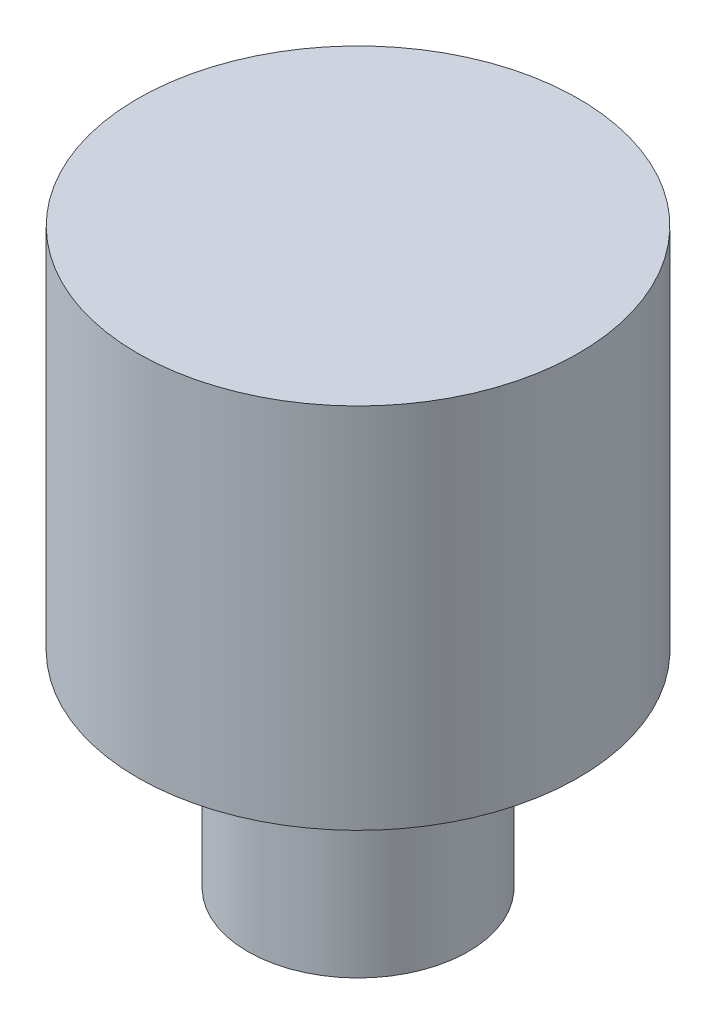
SolidWorks part; units mm, degrees
ref_plane "前基準面" through (0, 0, 0) normal (0, 0, 1) x (1, 0, 0)
ref_plane "上基準面" through (0, 0, 0) normal (0, 1, 0) x (1, 0, 0)
ref_plane "右基準面" through (0, 0, 0) normal (1, 0, 0) x (0, 0, -1)
sketch "草圖1" plane through (0, 0, 0) normal (0, 1, 0) x (1, 0, 0)
  circle A0 centre (0, 0) radius 1.5
extrude "填料-伸長1" add sketch "草圖1" along normal blind 2.8
sketch "草圖2" plane through (0, 2.8, 0) normal (0, 1, 0) x (1, 0, 0)
  circle A0 centre (0, 0) radius 3
extrude "填料-伸長2" add sketch "草圖2" along normal blind 5
